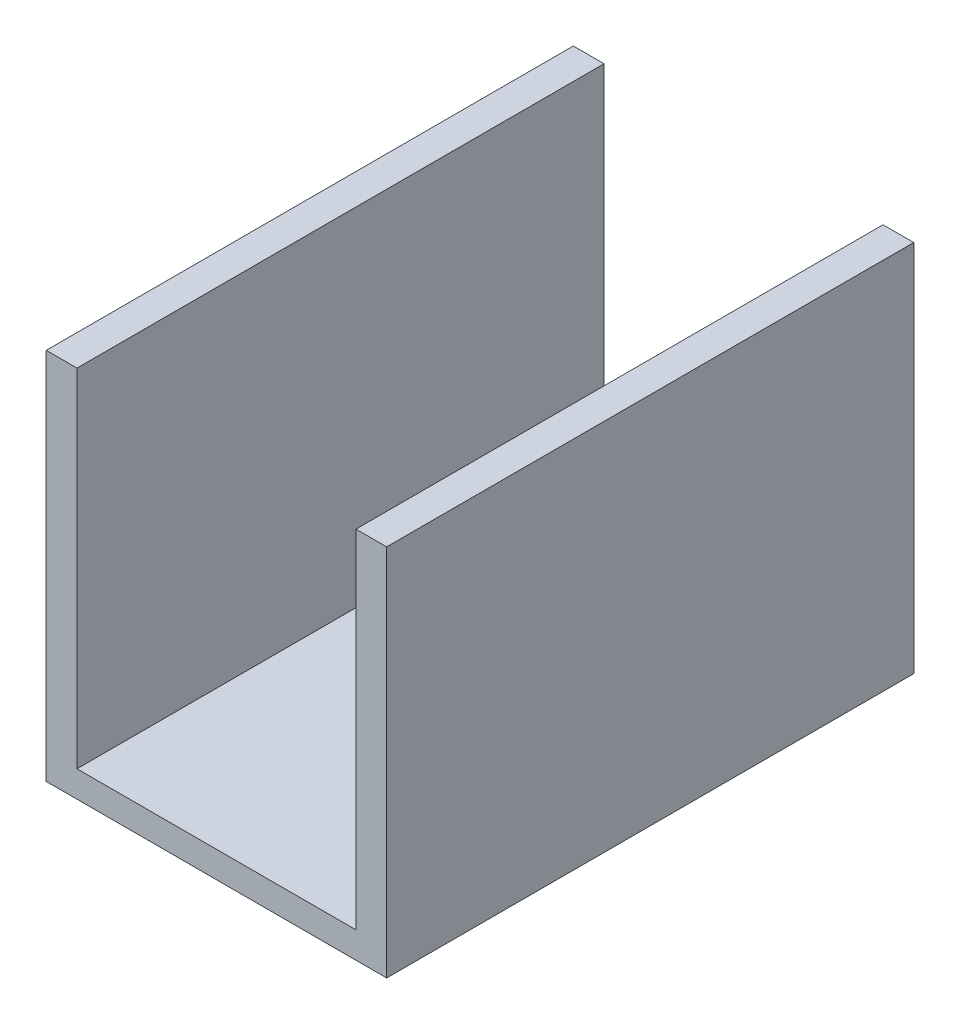
SolidWorks part; units mm, degrees
material "PLA"
ref_plane "Front Plane" through (0, 0, 0) normal (0, 0, 1) x (1, 0, 0)
ref_plane "Top Plane" through (0, 0, 0) normal (0, 1, 0) x (1, 0, 0)
ref_plane "Right Plane" through (0, 0, 0) normal (1, 0, 0) x (0, 0, -1)
sketch "Sketch2" plane through (0, 0, 0) normal (0, 0, 1) x (1, 0, 0)
  line L0 (-31.75, 0) -> (31.75, 0)
  line L1 (-31.75, 0) -> (-31.75, 79)
  line L2 (-31.75, 79) -> (-38.75, 79)
  line L3 (-38.75, 79) -> (-38.75, -6)
  line L7 (31.75, 79) -> (31.75, 0)
  line L8 (-38.75, -6) -> (38.75, -6)
  line L9 (38.75, -6) -> (38.75, 79)
  line L10 (38.75, 79) -> (31.75, 79)
  point P4 (0, 0)
  dimension "D1" = 63.5
  dimension "D2" = 7
  dimension "D3" = 7
  dimension "D4" = 85
  dimension "D5" = 6
  dimension "D6" = 85
extrude "Boss-Extrude1" add sketch "Sketch2" along normal mid plane 120
